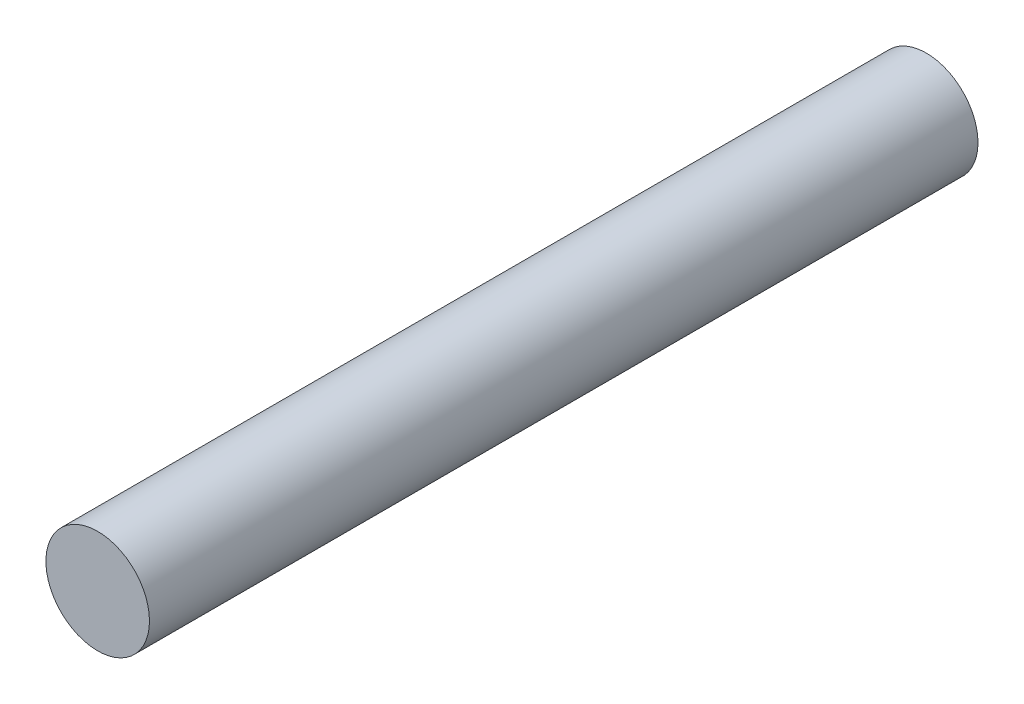
SolidWorks part; units mm, degrees
material "ABS"
ref_plane "Ön Düzlem" through (0, 0, 0) normal (0, 0, 1) x (1, 0, 0)
ref_plane "Üst Düzlem" through (0, 0, 0) normal (0, 1, 0) x (1, 0, 0)
ref_plane "Sağ Düzlem" through (0, 0, 0) normal (1, 0, 0) x (0, 0, -1)
sketch "Çizim1" plane through (0, 0, 0) normal (0, 0, 1) x (1, 0, 0)
  circle A0 centre (0, 0) radius 2.5
extrude "Yükseklik-Ekstrüzyon1" add sketch "Çizim1" along normal blind 40 contours A0
